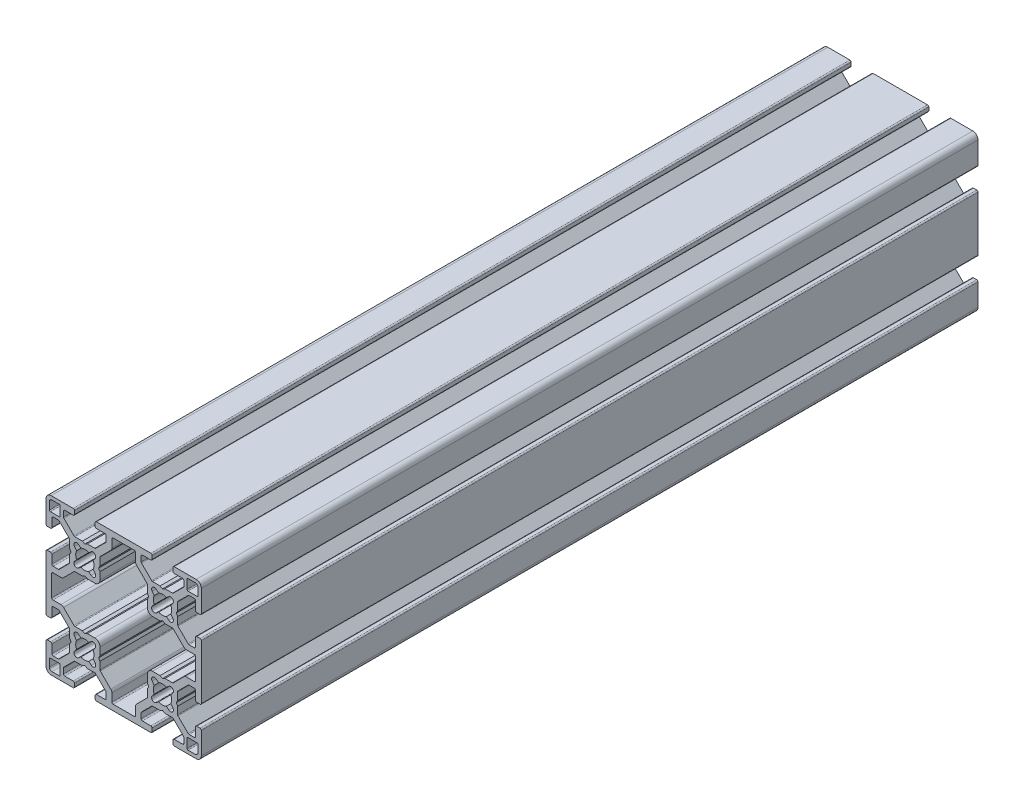
SolidWorks part; units mm, degrees
material "6105-T5 Aluminum"
ref_plane "Front Plane" through (0, 0, 0) normal (0, 0, 1) x (1, 0, 0)
ref_plane "Top Plane" through (0, 0, 0) normal (0, 1, 0) x (1, 0, 0)
ref_plane "Right Plane" through (0, 0, 0) normal (1, 0, 0) x (0, 0, -1)
sketch "Sketch1" plane through (0, 0, 0) normal (0, 0, 1) x (1, 0, 0)
  line L0 (12.8, -19.05) -> (12.8, -10.95)
  line L1 (9.2682, -19.55) -> (12.3, -19.55)
  line L2 (4.178, -24.0188) -> (8.2075, -19.9893)
  line L3 (0.95, -24.1653) -> (3.8245, -24.1653)
  line L4 (0, -24.6753) -> (0.95, -24.1653)
  line L5 (-0.95, -24.1653) -> (0, -24.6753)
  line L6 (-3.8347, -24.1653) -> (-0.95, -24.1653)
  line L7 (-5.8347, -29.1124) -> (-5.8347, -26.1653)
  line L8 (-5.3247, -30.0624) -> (-5.8347, -29.1124)
  line L9 (-5.8347, -31.0124) -> (-5.3247, -30.0624)
  line L10 (-5.8347, -33.8244) -> (-5.8347, -31.0124)
  line L11 (-10.0106, -38.2075) -> (-5.9811, -34.178)
  line L12 (-10.45, -42.2999) -> (-10.45, -39.2681)
  line L13 (-19.05, -42.7999) -> (-10.95, -42.7999)
  line L14 (-19.55, -39.2681) -> (-19.55, -42.2999)
  line L15 (-24.0188, -34.178) -> (-19.9893, -38.2075)
  line L16 (-24.1653, -31.0124) -> (-24.1653, -33.8244)
  line L17 (-24.6753, -30.0624) -> (-24.1653, -31.0124)
  line L18 (-24.1653, -29.1124) -> (-24.6753, -30.0624)
  line L19 (-24.1653, -26.1653) -> (-24.1653, -29.1124)
  line L20 (-29.0499, -24.1653) -> (-26.1653, -24.1653)
  line L21 (-29.9999, -24.6753) -> (-29.0499, -24.1653)
  line L22 (-30.9499, -24.1653) -> (-29.9999, -24.6753)
  line L23 (-33.8244, -24.1653) -> (-30.9499, -24.1653)
  line L24 (-38.2075, -19.9893) -> (-34.178, -24.0188)
  line L25 (-42.2999, -19.55) -> (-39.2681, -19.55)
  line L26 (-42.7999, -10.95) -> (-42.7999, -19.05)
  line L27 (-39.2681, -10.45) -> (-42.2999, -10.45)
  line L28 (-34.178, -5.9811) -> (-38.2075, -10.0106)
  line L29 (-30.9499, -5.8347) -> (-33.8244, -5.8347)
  line L30 (-29.9999, -5.3247) -> (-30.9499, -5.8347)
  line L31 (-29.0499, -5.8347) -> (-29.9999, -5.3247)
  line L32 (-26.1653, -5.8347) -> (-29.0499, -5.8347)
  line L33 (-24.1653, -1.0125) -> (-24.1653, -3.8347)
  line L34 (-24.6753, -0.0625) -> (-24.1653, -1.0125)
  line L35 (-24.1653, 0.8875) -> (-24.6753, -0.0625)
  line L36 (-24.1653, 3.8245) -> (-24.1653, 0.8875)
  line L37 (-19.9893, 8.2075) -> (-24.0188, 4.178)
  line L38 (-19.55, 12.3) -> (-19.55, 9.2682)
  line L39 (-10.95, 12.8) -> (-19.05, 12.8)
  line L40 (-10.45, 9.2682) -> (-10.45, 12.3)
  line L41 (-5.9811, 4.178) -> (-10.0106, 8.2075)
  line L42 (-5.8347, 0.8875) -> (-5.8347, 3.8245)
  line L43 (-5.3247, -0.0625) -> (-5.8347, 0.8875)
  line L44 (-5.8347, -1.0125) -> (-5.3247, -0.0625)
  line L45 (-5.8347, -3.8347) -> (-5.8347, -1.0125)
  line L46 (-0.95, -5.8347) -> (-3.8347, -5.8347)
  line L47 (0, -5.3247) -> (-0.95, -5.8347)
  line L48 (0.95, -5.8347) -> (0, -5.3247)
  line L49 (3.8245, -5.8347) -> (0.95, -5.8347)
  line L50 (8.2075, -10.0106) -> (4.178, -5.9811)
  line L51 (12.3, -10.45) -> (9.2682, -10.45)
  line L52 (-2.4733, -33.9799) -> (-1.4942, -33.1981)
  line L53 (-3.1981, -31.4942) -> (-3.9799, -32.4733)
  line L54 (-3.9799, -27.5266) -> (-3.1981, -28.5057)
  line L55 (-1.4942, -26.8018) -> (-2.4733, -26.02)
  line L56 (2.4733, -26.02) -> (1.4942, -26.8018)
  line L57 (3.1981, -28.5057) -> (3.9799, -27.5266)
  line L58 (3.9799, -32.4733) -> (3.1981, -31.4942)
  line L59 (1.4942, -33.1981) -> (2.4733, -33.9799)
  line L60 (-32.4733, -33.9799) -> (-31.4942, -33.1981)
  line L61 (-33.1981, -31.4942) -> (-33.9799, -32.4733)
  line L62 (-33.9799, -27.5266) -> (-33.1981, -28.5057)
  line L63 (-31.4942, -26.8018) -> (-32.4733, -26.02)
  line L64 (-27.5266, -26.02) -> (-28.5057, -26.8018)
  line L65 (-26.8018, -28.5057) -> (-26.02, -27.5266)
  line L66 (-26.02, -32.4733) -> (-26.8018, -31.4942)
  line L67 (-28.5057, -33.1981) -> (-27.5266, -33.9799)
  line L68 (-2.4733, -3.9799) -> (-1.4942, -3.1981)
  line L69 (-3.1981, -1.4942) -> (-3.9799, -2.4733)
  line L70 (-3.9799, 2.4733) -> (-3.1981, 1.4942)
  line L71 (-1.4942, 3.1981) -> (-2.4733, 3.9799)
  line L72 (2.4733, 3.9799) -> (1.4942, 3.1981)
  line L73 (3.1981, 1.4942) -> (3.9799, 2.4733)
  line L74 (3.9799, -2.4733) -> (3.1981, -1.4942)
  line L75 (1.4942, -3.1981) -> (2.4733, -3.9799)
  line L76 (-32.4733, -3.9799) -> (-31.4942, -3.1981)
  line L77 (-33.1981, -1.4942) -> (-33.9799, -2.4733)
  line L78 (-33.9799, 2.4733) -> (-33.1981, 1.4942)
  line L79 (-31.4942, 3.1981) -> (-32.4733, 3.9799)
  line L80 (-27.5266, 3.9799) -> (-28.5057, 3.1981)
  line L81 (-26.8018, 1.4942) -> (-26.02, 2.4733)
  line L82 (-26.02, -2.4733) -> (-26.8018, -1.4942)
  line L83 (-28.5057, -3.1981) -> (-27.5266, -3.9799)
  line L84 (-39.4999, 9.88) -> (-39.4999, 13.319)
  line L85 (-43.3189, 9.5) -> (-39.8799, 9.5)
  line L86 (-43.6999, 12.7) -> (-43.6999, 9.881)
  line L87 (-39.8809, 13.7) -> (-42.6999, 13.7)
  line L88 (12.7, 13.7) -> (9.881, 13.7)
  line L89 (13.7, 9.881) -> (13.7, 12.7)
  line L90 (9.88, 9.5) -> (13.319, 9.5)
  line L91 (9.5, 13.319) -> (9.5, 9.88)
  line L92 (9.5, -39.8799) -> (9.5, -43.3189)
  line L93 (13.319, -39.4999) -> (9.88, -39.4999)
  line L94 (13.7, -42.6999) -> (13.7, -39.8809)
  line L95 (9.881, -43.6999) -> (12.7, -43.6999)
  line L96 (-39.8799, -39.4999) -> (-43.3189, -39.4999)
  line L97 (-39.4999, -43.3189) -> (-39.4999, -39.8799)
  line L98 (-42.6999, -43.6999) -> (-39.8809, -43.6999)
  line L99 (-43.6999, -39.8809) -> (-43.6999, -42.6999)
  line L100 (-44.4999, -25.9999) -> (-43.2424, -25.9999)
  line L101 (-42.7424, -25.4999) -> (-42.7424, -22.2674)
  line L102 (-42.2427, -21.75) -> (-40.2601, -21.75)
  line L103 (-39.9066, -21.8964) -> (-35.9811, -25.8219)
  line L104 (-35.8346, -26.1755) -> (-35.8346, -29.1124)
  line L105 (-35.8346, -29.1124) -> (-35.3246, -30.0624)
  line L106 (-35.3246, -30.0624) -> (-35.8346, -31.0124)
  line L107 (-35.8346, -31.0124) -> (-35.8346, -33.8244)
  line L108 (-35.9811, -34.178) -> (-39.9066, -38.1035)
  line L109 (-40.2601, -38.2499) -> (-42.2427, -38.2499)
  line L110 (-42.7424, -37.7325) -> (-42.7424, -34.4999)
  line L111 (-43.2424, -33.9999) -> (-44.4999, -33.9999)
  line L112 (-44.9999, -34.4999) -> (-44.9999, -42.9999)
  line L113 (-42.9999, -44.9999) -> (-34.4999, -44.9999)
  line L114 (-33.9999, -44.4999) -> (-33.9999, -43.2424)
  line L115 (-34.4999, -42.7424) -> (-37.7325, -42.7424)
  line L116 (-38.2499, -42.2427) -> (-38.2499, -40.2601)
  line L117 (-38.1035, -39.9066) -> (-34.178, -35.9811)
  line L118 (-33.8244, -35.8346) -> (-30.9499, -35.8346)
  line L119 (-30.9499, -35.8346) -> (-29.9999, -35.3246)
  line L120 (-29.9999, -35.3246) -> (-29.0499, -35.8346)
  line L121 (-29.0499, -35.8346) -> (-26.1755, -35.8346)
  line L122 (-25.8219, -35.9811) -> (-21.8964, -39.9066)
  line L123 (-21.75, -40.2601) -> (-21.75, -42.2427)
  line L124 (-22.2674, -42.7424) -> (-25.4999, -42.7424)
  line L125 (-25.9999, -43.2424) -> (-25.9999, -44.4999)
  line L126 (-25.4999, -44.9999) -> (-4.5, -44.9999)
  line L127 (-4, -44.4999) -> (-4, -43.2424)
  line L128 (-4.5, -42.7424) -> (-7.7325, -42.7424)
  line L129 (-8.25, -42.2427) -> (-8.25, -40.2601)
  line L130 (-8.1035, -39.9066) -> (-4.178, -35.9811)
  line L131 (-3.8245, -35.8346) -> (-0.95, -35.8346)
  line L132 (-0.95, -35.8346) -> (0, -35.3246)
  line L133 (0, -35.3246) -> (0.95, -35.8346)
  line L134 (0.95, -35.8346) -> (3.8245, -35.8346)
  line L135 (4.178, -35.9811) -> (8.1035, -39.9066)
  line L136 (8.25, -40.2601) -> (8.25, -42.2427)
  line L137 (7.7325, -42.7424) -> (4.5, -42.7424)
  line L138 (4, -43.2424) -> (4, -44.4999)
  line L139 (4.5, -44.9999) -> (13, -44.9999)
  line L140 (15, -42.9999) -> (15, -34.4999)
  line L141 (14.5, -33.9999) -> (13.2425, -33.9999)
  line L142 (12.7425, -34.4999) -> (12.7425, -37.7325)
  line L143 (12.2428, -38.2499) -> (10.2602, -38.2499)
  line L144 (9.9067, -38.1035) -> (5.9811, -34.178)
  line L145 (5.8347, -33.8244) -> (5.8347, -31.0124)
  line L146 (5.8347, -31.0124) -> (5.3247, -30.0624)
  line L147 (5.3247, -30.0624) -> (5.8347, -29.1124)
  line L148 (5.8347, -29.1124) -> (5.8347, -26.1755)
  line L149 (5.9811, -25.8219) -> (9.9067, -21.8964)
  line L150 (10.2602, -21.75) -> (12.2428, -21.75)
  line L151 (12.7425, -22.2674) -> (12.7425, -25.4999)
  line L152 (13.2425, -25.9999) -> (14.5, -25.9999)
  line L153 (15, -25.4999) -> (15, -4.5)
  line L154 (14.5, -4) -> (13.2425, -4)
  line L155 (12.7425, -4.5) -> (12.7425, -7.7325)
  line L156 (12.2428, -8.25) -> (10.2602, -8.25)
  line L157 (9.9067, -8.1035) -> (5.9811, -4.178)
  line L158 (5.8347, -3.8245) -> (5.8347, -1.0125)
  line L159 (5.8347, -1.0125) -> (5.3247, -0.0625)
  line L160 (5.3247, -0.0625) -> (5.8347, 0.8875)
  line L161 (5.8347, 0.8875) -> (5.8347, 3.8245)
  line L162 (5.9811, 4.178) -> (9.9067, 8.1035)
  line L163 (10.2602, 8.25) -> (12.2428, 8.25)
  line L164 (12.7425, 7.7325) -> (12.7425, 4.5)
  line L165 (13.2425, 4) -> (14.5, 4)
  line L166 (15, 4.5) -> (15, 13)
  line L167 (13, 15) -> (4.5, 15)
  line L168 (4, 14.5) -> (4, 13.2425)
  line L169 (4.5, 12.7425) -> (7.7325, 12.7425)
  line L170 (8.25, 12.2428) -> (8.25, 10.2602)
  line L171 (8.1035, 9.9067) -> (4.178, 5.9811)
  line L172 (3.8245, 5.8347) -> (0.95, 5.8347)
  line L173 (0.95, 5.8347) -> (0, 5.3247)
  line L174 (0, 5.3247) -> (-0.95, 5.8347)
  line L175 (-0.95, 5.8347) -> (-3.8245, 5.8347)
  line L176 (-4.178, 5.9811) -> (-8.1035, 9.9067)
  line L177 (-8.25, 10.2602) -> (-8.25, 12.2428)
  line L178 (-7.7325, 12.7425) -> (-4.5, 12.7425)
  line L179 (-4, 13.2425) -> (-4, 14.5)
  line L180 (-4.5, 15) -> (-25.4999, 15)
  line L181 (-25.9999, 14.5) -> (-25.9999, 13.2425)
  line L182 (-25.4999, 12.7425) -> (-22.2674, 12.7425)
  line L183 (-21.75, 12.2428) -> (-21.75, 10.2602)
  line L184 (-21.8964, 9.9067) -> (-25.8219, 5.9811)
  line L185 (-26.1755, 5.8347) -> (-29.0499, 5.8347)
  line L186 (-29.0499, 5.8347) -> (-29.9999, 5.3247)
  line L187 (-29.9999, 5.3247) -> (-30.9499, 5.8347)
  line L188 (-30.9499, 5.8347) -> (-33.8244, 5.8347)
  line L189 (-34.178, 5.9811) -> (-38.1035, 9.9067)
  line L190 (-38.2499, 10.2602) -> (-38.2499, 12.2428)
  line L191 (-37.7325, 12.7425) -> (-34.4999, 12.7425)
  line L192 (-33.9999, 13.2425) -> (-33.9999, 14.5)
  line L193 (-34.4999, 15) -> (-42.9999, 15)
  line L194 (-44.9999, 13) -> (-44.9999, 4.5)
  line L195 (-44.4999, 4) -> (-43.2424, 4)
  line L196 (-42.7424, 4.5) -> (-42.7424, 7.7325)
  line L197 (-42.2427, 8.25) -> (-40.2601, 8.25)
  line L198 (-39.9066, 8.1035) -> (-35.9811, 4.178)
  line L199 (-35.8346, 3.8245) -> (-35.8346, 0.8875)
  line L200 (-35.8346, 0.8875) -> (-35.3246, -0.0625)
  line L201 (-35.3246, -0.0625) -> (-35.8346, -1.0125)
  line L202 (-35.8346, -1.0125) -> (-35.8346, -3.8245)
  line L203 (-35.9811, -4.178) -> (-39.9066, -8.1035)
  line L204 (-40.2601, -8.25) -> (-42.2427, -8.25)
  line L205 (-42.7424, -7.7325) -> (-42.7424, -4.5)
  line L206 (-43.2424, -4) -> (-44.4999, -4)
  line L207 (-44.9999, -4.5) -> (-44.9999, -25.4999)
  arc A0 (12.8, -10.95) -> (12.3, -10.45) centre (12.3, -10.95) ccw
  arc A1 (12.3, -19.55) -> (12.8, -19.05) centre (12.3, -19.05) ccw
  arc A2 (9.2682, -19.55) -> (8.2075, -19.9893) centre (9.2682, -21.05) ccw
  arc A3 (3.8245, -24.1653) -> (4.178, -24.0188) centre (3.8245, -23.6653) ccw
  arc A4 (-3.8347, -24.1653) -> (-5.8347, -26.1653) centre (-3.8347, -26.1653) ccw
  arc A5 (-5.9811, -34.178) -> (-5.8347, -33.8244) centre (-6.3347, -33.8244) ccw
  arc A6 (-10.0106, -38.2075) -> (-10.45, -39.2681) centre (-8.95, -39.2681) ccw
  arc A7 (-10.95, -42.7999) -> (-10.45, -42.2999) centre (-10.95, -42.2999) ccw
  arc A8 (-19.55, -42.2999) -> (-19.05, -42.7999) centre (-19.05, -42.2999) ccw
  arc A9 (-19.55, -39.2681) -> (-19.9893, -38.2075) centre (-21.05, -39.2681) ccw
  arc A10 (-24.1653, -33.8244) -> (-24.0188, -34.178) centre (-23.6653, -33.8244) ccw
  arc A11 (-24.1653, -26.1653) -> (-26.1653, -24.1653) centre (-26.1653, -26.1653) ccw
  arc A12 (-34.178, -24.0188) -> (-33.8244, -24.1653) centre (-33.8244, -23.6653) ccw
  arc A13 (-38.2075, -19.9893) -> (-39.2681, -19.55) centre (-39.2681, -21.05) ccw
  arc A14 (-42.7999, -19.05) -> (-42.2999, -19.55) centre (-42.2999, -19.05) ccw
  arc A15 (-42.2999, -10.45) -> (-42.7999, -10.95) centre (-42.2999, -10.95) ccw
  arc A16 (-39.2681, -10.45) -> (-38.2075, -10.0106) centre (-39.2681, -8.95) ccw
  arc A17 (-33.8244, -5.8347) -> (-34.178, -5.9811) centre (-33.8244, -6.3347) ccw
  arc A18 (-26.1653, -5.8347) -> (-24.1653, -3.8347) centre (-26.1653, -3.8347) ccw
  arc A19 (-24.0188, 4.178) -> (-24.1653, 3.8245) centre (-23.6653, 3.8245) ccw
  arc A20 (-19.9893, 8.2075) -> (-19.55, 9.2682) centre (-21.05, 9.2682) ccw
  arc A21 (-19.05, 12.8) -> (-19.55, 12.3) centre (-19.05, 12.3) ccw
  arc A22 (-10.45, 12.3) -> (-10.95, 12.8) centre (-10.95, 12.3) ccw
  arc A23 (-10.45, 9.2682) -> (-10.0106, 8.2075) centre (-8.95, 9.2682) ccw
  arc A24 (-5.8347, 3.8245) -> (-5.9811, 4.178) centre (-6.3347, 3.8245) ccw
  arc A25 (-5.8347, -3.8347) -> (-3.8347, -5.8347) centre (-3.8347, -3.8347) ccw
  arc A26 (4.178, -5.9811) -> (3.8245, -5.8347) centre (3.8245, -6.3347) ccw
  arc A27 (8.2075, -10.0106) -> (9.2682, -10.45) centre (9.2682, -8.95) ccw
  arc A28 (-1.4942, -33.1981) -> (1.4942, -33.1981) centre (0, -29.9999) ccw
  arc A29 (-3.9799, -32.4733) -> (-2.4733, -33.9799) centre (-3.1422, -33.1422) ccw
  arc A30 (-3.1981, -28.5057) -> (-3.1981, -31.4942) centre (0, -29.9999) ccw
  arc A31 (-2.4733, -26.02) -> (-3.9799, -27.5266) centre (-3.1422, -26.8577) ccw
  arc A32 (1.4942, -26.8018) -> (-1.4942, -26.8018) centre (0, -29.9999) ccw
  arc A33 (3.9799, -27.5266) -> (2.4733, -26.02) centre (3.1422, -26.8577) ccw
  arc A34 (3.1981, -31.4942) -> (3.1981, -28.5057) centre (0, -29.9999) ccw
  arc A35 (2.4733, -33.9799) -> (3.9799, -32.4733) centre (3.1422, -33.1422) ccw
  arc A36 (-31.4942, -33.1981) -> (-28.5057, -33.1981) centre (-29.9999, -29.9999) ccw
  arc A37 (-33.9799, -32.4733) -> (-32.4733, -33.9799) centre (-33.1422, -33.1422) ccw
  arc A38 (-33.1981, -28.5057) -> (-33.1981, -31.4942) centre (-29.9999, -29.9999) ccw
  arc A39 (-32.4733, -26.02) -> (-33.9799, -27.5266) centre (-33.1422, -26.8577) ccw
  arc A40 (-28.5057, -26.8018) -> (-31.4942, -26.8018) centre (-29.9999, -29.9999) ccw
  arc A41 (-26.02, -27.5266) -> (-27.5266, -26.02) centre (-26.8577, -26.8577) ccw
  arc A42 (-26.8018, -31.4942) -> (-26.8018, -28.5057) centre (-29.9999, -29.9999) ccw
  arc A43 (-27.5266, -33.9799) -> (-26.02, -32.4733) centre (-26.8577, -33.1422) ccw
  arc A44 (-1.4942, -3.1981) -> (1.4942, -3.1981) centre (0, 0) ccw
  arc A45 (-3.9799, -2.4733) -> (-2.4733, -3.9799) centre (-3.1422, -3.1422) ccw
  arc A46 (-3.1981, 1.4942) -> (-3.1981, -1.4942) centre (0, 0) ccw
  arc A47 (-2.4733, 3.9799) -> (-3.9799, 2.4733) centre (-3.1422, 3.1422) ccw
  arc A48 (1.4942, 3.1981) -> (-1.4942, 3.1981) centre (0, 0) ccw
  arc A49 (3.9799, 2.4733) -> (2.4733, 3.9799) centre (3.1422, 3.1422) ccw
  arc A50 (3.1981, -1.4942) -> (3.1981, 1.4942) centre (0, 0) ccw
  arc A51 (2.4733, -3.9799) -> (3.9799, -2.4733) centre (3.1422, -3.1422) ccw
  arc A52 (-31.4942, -3.1981) -> (-28.5057, -3.1981) centre (-29.9999, 0) ccw
  arc A53 (-33.9799, -2.4733) -> (-32.4733, -3.9799) centre (-33.1422, -3.1422) ccw
  arc A54 (-33.1981, 1.4942) -> (-33.1981, -1.4942) centre (-29.9999, 0) ccw
  arc A55 (-32.4733, 3.9799) -> (-33.9799, 2.4733) centre (-33.1422, 3.1422) ccw
  arc A56 (-28.5057, 3.1981) -> (-31.4942, 3.1981) centre (-29.9999, 0) ccw
  arc A57 (-26.02, 2.4733) -> (-27.5266, 3.9799) centre (-26.8577, 3.1422) ccw
  arc A58 (-26.8018, -1.4942) -> (-26.8018, 1.4942) centre (-29.9999, 0) ccw
  arc A59 (-27.5266, -3.9799) -> (-26.02, -2.4733) centre (-26.8577, -3.1422) ccw
  arc A60 (-39.4999, 13.319) -> (-39.8809, 13.7) centre (-39.8809, 13.319) ccw
  arc A61 (-39.8799, 9.5) -> (-39.4999, 9.88) centre (-39.8799, 9.88) ccw
  arc A62 (-43.6999, 9.881) -> (-43.3189, 9.5) centre (-43.3189, 9.881) ccw
  arc A63 (-42.6999, 13.7) -> (-43.6999, 12.7) centre (-42.6999, 12.7) ccw
  arc A64 (9.881, 13.7) -> (9.5, 13.319) centre (9.881, 13.319) ccw
  arc A65 (13.7, 12.7) -> (12.7, 13.7) centre (12.7, 12.7) ccw
  arc A66 (13.319, 9.5) -> (13.7, 9.881) centre (13.319, 9.881) ccw
  arc A67 (9.5, 9.88) -> (9.88, 9.5) centre (9.88, 9.88) ccw
  arc A68 (9.5, -43.3189) -> (9.881, -43.6999) centre (9.881, -43.3189) ccw
  arc A69 (9.88, -39.4999) -> (9.5, -39.8799) centre (9.88, -39.8799) ccw
  arc A70 (13.7, -39.8809) -> (13.319, -39.4999) centre (13.319, -39.8809) ccw
  arc A71 (12.7, -43.6999) -> (13.7, -42.6999) centre (12.7, -42.6999) ccw
  arc A72 (-43.3189, -39.4999) -> (-43.6999, -39.8809) centre (-43.3189, -39.8809) ccw
  arc A73 (-39.4999, -39.8799) -> (-39.8799, -39.4999) centre (-39.8799, -39.8799) ccw
  arc A74 (-39.8809, -43.6999) -> (-39.4999, -43.3189) centre (-39.8809, -43.3189) ccw
  arc A75 (-43.6999, -42.6999) -> (-42.6999, -43.6999) centre (-42.6999, -42.6999) ccw
  arc A76 (-44.9999, -25.4999) -> (-44.4999, -25.9999) centre (-44.4999, -25.4999) ccw
  arc A77 (-43.2424, -25.9999) -> (-42.7424, -25.4999) centre (-43.2424, -25.4999) ccw
  arc A78 (-42.2427, -21.75) -> (-42.7424, -22.2674) centre (-42.2427, -22.25) ccw
  arc A79 (-39.9066, -21.8964) -> (-40.2601, -21.75) centre (-40.2601, -22.25) ccw
  arc A80 (-35.8346, -26.1755) -> (-35.9811, -25.8219) centre (-36.3346, -26.1755) ccw
  arc A81 (-35.9811, -34.178) -> (-35.8346, -33.8244) centre (-36.3346, -33.8244) ccw
  arc A82 (-40.2601, -38.2499) -> (-39.9066, -38.1035) centre (-40.2601, -37.7499) ccw
  arc A83 (-42.7424, -37.7325) -> (-42.2427, -38.2499) centre (-42.2427, -37.7499) ccw
  arc A84 (-42.7424, -34.4999) -> (-43.2424, -33.9999) centre (-43.2424, -34.4999) ccw
  arc A85 (-44.4999, -33.9999) -> (-44.9999, -34.4999) centre (-44.4999, -34.4999) ccw
  arc A86 (-44.9999, -42.9999) -> (-42.9999, -44.9999) centre (-42.9999, -42.9999) ccw
  arc A87 (-34.4999, -44.9999) -> (-33.9999, -44.4999) centre (-34.4999, -44.4999) ccw
  arc A88 (-33.9999, -43.2424) -> (-34.4999, -42.7424) centre (-34.4999, -43.2424) ccw
  arc A89 (-38.2499, -42.2427) -> (-37.7325, -42.7424) centre (-37.7499, -42.2427) ccw
  arc A90 (-38.1035, -39.9066) -> (-38.2499, -40.2601) centre (-37.7499, -40.2601) ccw
  arc A91 (-33.8244, -35.8346) -> (-34.178, -35.9811) centre (-33.8244, -36.3346) ccw
  arc A92 (-25.8219, -35.9811) -> (-26.1755, -35.8346) centre (-26.1755, -36.3346) ccw
  arc A93 (-21.75, -40.2601) -> (-21.8964, -39.9066) centre (-22.25, -40.2601) ccw
  arc A94 (-22.2674, -42.7424) -> (-21.75, -42.2427) centre (-22.25, -42.2427) ccw
  arc A95 (-25.4999, -42.7424) -> (-25.9999, -43.2424) centre (-25.4999, -43.2424) ccw
  arc A96 (-25.9999, -44.4999) -> (-25.4999, -44.9999) centre (-25.4999, -44.4999) ccw
  arc A97 (-4.5, -44.9999) -> (-4, -44.4999) centre (-4.5, -44.4999) ccw
  arc A98 (-4, -43.2424) -> (-4.5, -42.7424) centre (-4.5, -43.2424) ccw
  arc A99 (-8.25, -42.2427) -> (-7.7325, -42.7424) centre (-7.75, -42.2427) ccw
  arc A100 (-8.1035, -39.9066) -> (-8.25, -40.2601) centre (-7.75, -40.2601) ccw
  arc A101 (-3.8245, -35.8346) -> (-4.178, -35.9811) centre (-3.8245, -36.3346) ccw
  arc A102 (4.178, -35.9811) -> (3.8245, -35.8346) centre (3.8245, -36.3346) ccw
  arc A103 (8.25, -40.2601) -> (8.1035, -39.9066) centre (7.75, -40.2601) ccw
  arc A104 (7.7325, -42.7424) -> (8.25, -42.2427) centre (7.75, -42.2427) ccw
  arc A105 (4.5, -42.7424) -> (4, -43.2424) centre (4.5, -43.2424) ccw
  arc A106 (4, -44.4999) -> (4.5, -44.9999) centre (4.5, -44.4999) ccw
  arc A107 (13, -44.9999) -> (15, -42.9999) centre (13, -42.9999) ccw
  arc A108 (15, -34.4999) -> (14.5, -33.9999) centre (14.5, -34.4999) ccw
  arc A109 (13.2425, -33.9999) -> (12.7425, -34.4999) centre (13.2425, -34.4999) ccw
  arc A110 (12.2428, -38.2499) -> (12.7425, -37.7325) centre (12.2428, -37.7499) ccw
  arc A111 (9.9067, -38.1035) -> (10.2602, -38.2499) centre (10.2602, -37.7499) ccw
  arc A112 (5.8347, -33.8244) -> (5.9811, -34.178) centre (6.3347, -33.8244) ccw
  arc A113 (5.9811, -25.8219) -> (5.8347, -26.1755) centre (6.3347, -26.1755) ccw
  arc A114 (10.2602, -21.75) -> (9.9067, -21.8964) centre (10.2602, -22.25) ccw
  arc A115 (12.7425, -22.2674) -> (12.2428, -21.75) centre (12.2428, -22.25) ccw
  arc A116 (12.7425, -25.4999) -> (13.2425, -25.9999) centre (13.2425, -25.4999) ccw
  arc A117 (14.5, -25.9999) -> (15, -25.4999) centre (14.5, -25.4999) ccw
  arc A118 (15, -4.5) -> (14.5, -4) centre (14.5, -4.5) ccw
  arc A119 (13.2425, -4) -> (12.7425, -4.5) centre (13.2425, -4.5) ccw
  arc A120 (12.2428, -8.25) -> (12.7425, -7.7325) centre (12.2428, -7.75) ccw
  arc A121 (9.9067, -8.1035) -> (10.2602, -8.25) centre (10.2602, -7.75) ccw
  arc A122 (5.8347, -3.8245) -> (5.9811, -4.178) centre (6.3347, -3.8245) ccw
  arc A123 (5.9811, 4.178) -> (5.8347, 3.8245) centre (6.3347, 3.8245) ccw
  arc A124 (10.2602, 8.25) -> (9.9067, 8.1035) centre (10.2602, 7.75) ccw
  arc A125 (12.7425, 7.7325) -> (12.2428, 8.25) centre (12.2428, 7.75) ccw
  arc A126 (12.7425, 4.5) -> (13.2425, 4) centre (13.2425, 4.5) ccw
  arc A127 (14.5, 4) -> (15, 4.5) centre (14.5, 4.5) ccw
  arc A128 (15, 13) -> (13, 15) centre (13, 13) ccw
  arc A129 (4.5, 15) -> (4, 14.5) centre (4.5, 14.5) ccw
  arc A130 (4, 13.2425) -> (4.5, 12.7425) centre (4.5, 13.2425) ccw
  arc A131 (8.25, 12.2428) -> (7.7325, 12.7425) centre (7.75, 12.2428) ccw
  arc A132 (8.1035, 9.9067) -> (8.25, 10.2602) centre (7.75, 10.2602) ccw
  arc A133 (3.8245, 5.8347) -> (4.178, 5.9811) centre (3.8245, 6.3347) ccw
  arc A134 (-4.178, 5.9811) -> (-3.8245, 5.8347) centre (-3.8245, 6.3347) ccw
  arc A135 (-8.25, 10.2602) -> (-8.1035, 9.9067) centre (-7.75, 10.2602) ccw
  arc A136 (-7.7325, 12.7425) -> (-8.25, 12.2428) centre (-7.75, 12.2428) ccw
  arc A137 (-4.5, 12.7425) -> (-4, 13.2425) centre (-4.5, 13.2425) ccw
  arc A138 (-4, 14.5) -> (-4.5, 15) centre (-4.5, 14.5) ccw
  arc A139 (-25.4999, 15) -> (-25.9999, 14.5) centre (-25.4999, 14.5) ccw
  arc A140 (-25.9999, 13.2425) -> (-25.4999, 12.7425) centre (-25.4999, 13.2425) ccw
  arc A141 (-21.75, 12.2428) -> (-22.2674, 12.7425) centre (-22.25, 12.2428) ccw
  arc A142 (-21.8964, 9.9067) -> (-21.75, 10.2602) centre (-22.25, 10.2602) ccw
  arc A143 (-26.1755, 5.8347) -> (-25.8219, 5.9811) centre (-26.1755, 6.3347) ccw
  arc A144 (-34.178, 5.9811) -> (-33.8244, 5.8347) centre (-33.8244, 6.3347) ccw
  arc A145 (-38.2499, 10.2602) -> (-38.1035, 9.9067) centre (-37.7499, 10.2602) ccw
  arc A146 (-37.7325, 12.7425) -> (-38.2499, 12.2428) centre (-37.7499, 12.2428) ccw
  arc A147 (-34.4999, 12.7425) -> (-33.9999, 13.2425) centre (-34.4999, 13.2425) ccw
  arc A148 (-33.9999, 14.5) -> (-34.4999, 15) centre (-34.4999, 14.5) ccw
  arc A149 (-42.9999, 15) -> (-44.9999, 13) centre (-42.9999, 13) ccw
  arc A150 (-44.9999, 4.5) -> (-44.4999, 4) centre (-44.4999, 4.5) ccw
  arc A151 (-43.2424, 4) -> (-42.7424, 4.5) centre (-43.2424, 4.5) ccw
  arc A152 (-42.2427, 8.25) -> (-42.7424, 7.7325) centre (-42.2427, 7.75) ccw
  arc A153 (-39.9066, 8.1035) -> (-40.2601, 8.25) centre (-40.2601, 7.75) ccw
  arc A154 (-35.8346, 3.8245) -> (-35.9811, 4.178) centre (-36.3346, 3.8245) ccw
  arc A155 (-35.9811, -4.178) -> (-35.8346, -3.8245) centre (-36.3346, -3.8245) ccw
  arc A156 (-40.2601, -8.25) -> (-39.9066, -8.1035) centre (-40.2601, -7.75) ccw
  arc A157 (-42.7424, -7.7325) -> (-42.2427, -8.25) centre (-42.2427, -7.75) ccw
  arc A158 (-42.7424, -4.5) -> (-43.2424, -4) centre (-43.2424, -4.5) ccw
  arc A159 (-44.4999, -4) -> (-44.9999, -4.5) centre (-44.4999, -4.5) ccw
extrude "Extrude1" add sketch "Sketch1" against normal blind 300
